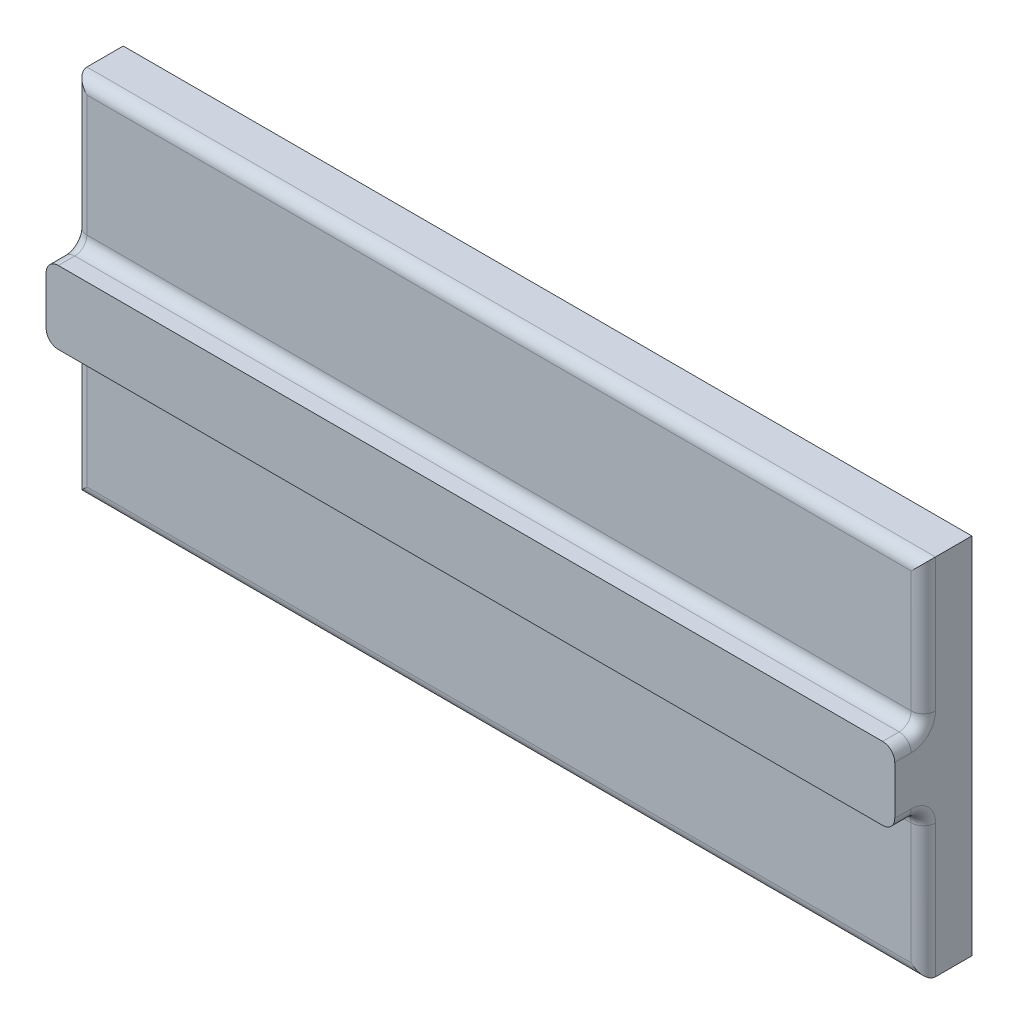
SolidWorks part; units mm, degrees
ref_plane "Alzado" through (0, 0, 0) normal (0, 0, 1) x (1, 0, 0)
ref_plane "Planta" through (0, 0, 0) normal (0, 1, 0) x (1, 0, 0)
ref_plane "Vista lateral" through (0, 0, 0) normal (1, 0, 0) x (0, 0, -1)
sketch "Croquis1" plane through (0, 0, 0) normal (1, 0, 0) x (0, 0, -1)
  line L0 (-21.7896, 0) -> (-21.7896, 15)
  line L1 (10, -75) -> (-10, -75)
  line L2 (10, -75) -> (10, 75)
  line L3 (10, 75) -> (-10, 75)
  line L4 (-10, -75) -> (-10, -15)
  line L5 (10, -75) -> (-10, 75) construction
  line L6 (10, 75) -> (-10, -75) construction
  line L7 (-21.7896, 15) -> (-10, 15)
  line L8 (-21.7896, 0) -> (-21.7896, -15)
  line L9 (-21.7896, -15) -> (-10, -15)
  line L10 (-10, 15) -> (-10, 75)
  point P0 (0, 0)
  dimension "D1" = 20
  dimension "D2" = 150
extrude "Saliente-Extruir1" add sketch "Croquis1" along normal mid plane 350
fillet "Redondeo1" radius 5 12 edges at (175, 15, 15.8948) (-175, 15, 15.8948) (175, -15, 15.8948) (-175, -15, 15.8948) (0, 75, 10) (175, 45, 10) (0, 15, 10) (-175, 45, 10) (0, -15, 10) (175, -45, 10) (0, -75, 10) (-175, -45, 10)
